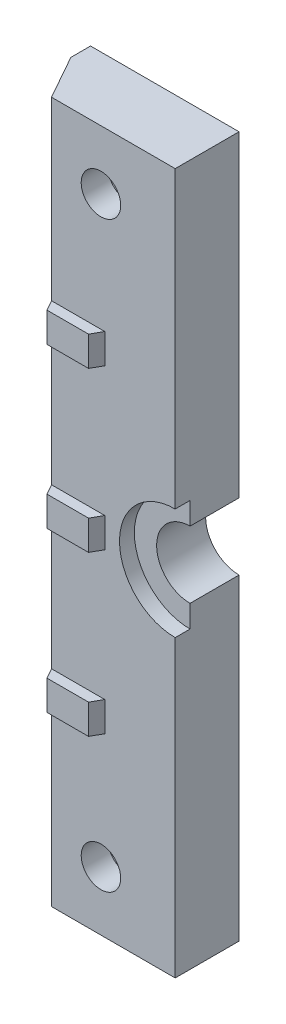
SolidWorks part; units mm, degrees
material "6061-T6 (SS)"
ref_plane "Front Plane" through (0, 0, 0) normal (0, 0, 1) x (1, 0, 0)
ref_plane "Top Plane" through (0, 0, 0) normal (0, 1, 0) x (1, 0, 0)
ref_plane "Right Plane" through (0, 0, 0) normal (1, 0, 0) x (0, 0, -1)
sketch "Sketch1" plane through (0, 0, 0) normal (0, 1, 0) x (1, 0, 0)
  line L0 (0, 0) -> (0, 10.922)
  line L1 (0, 10.922) -> (-25.4, 10.922)
  line L2 (-25.4, 10.922) -> (-25.4, 7.5565)
  line L3 (-25.4, 7.5565) -> (-21.1557, 0)
  line L4 (-21.1557, 0) -> (0, 0)
  dimension "D1" = 25.4
  dimension "D2" = 10.922
  dimension "D3" = 150.678
  dimension "D4" = 3.3655
extrude "Boss-Extrude1" add sketch "Sketch1" along normal blind 119.888
sketch "Sketch2" plane through (0, 0, -10.922) normal (0, 0, -1) x (-1, 0, 0)
  line L0 (12.7, 119.888) -> (12.7, 0) construction
  line L1 (0, 119.888) -> (25.4, 119.888) construction
  line L2 (0, 0) -> (25.4, 0) construction
  line L4 (0, 119.888) -> (0, 0) construction
  line L5 (0, 59.944) -> (25.4, 59.944) construction
  line L6 (25.4, 119.888) -> (25.4, 0) construction
  point P12 (12.7, 10.1155)
  point P14 (12.7, 109.7724)
  dimension "D1" = 49.8285
hole_wizard "CBORE for 1/4 Socket Head Cap Screw1" positions "Sketch2" profile "Sketch3" counterbore size "1/4" standard "ANSI Inch" end condition through all
sketch "Sketch3" plane through (-12.7, 109.7724, -10.922) normal (1, 0, 0) x (0, 1, 0)
  line L0 (0, 0) -> (0, 10.922)
  line L1 (0, 10.922) -> (3.3782, 10.922)
  line L3 (3.3782, 10.922) -> (3.3782, 6.35)
  line L4 (3.3782, 6.35) -> (5.5562, 6.35)
  line L5 (5.5562, 6.35) -> (5.5563, 0)
  line L7 (5.5563, 0) -> (0, 0)
  line L11 (0, -6.35) -> (0, 107.95) construction
  dimension "Thru Hole Dia." = 6.7564
  dimension "Thru Hole Depth" = 10.922
  dimension "C'Bore Dia." = 11.1125
  dimension "C'Bore Depth" = 6.35
sketch "Sketch4" plane through (0, 0, -10.922) normal (0, 0, -1) x (-1, 0, 0)
  line L0 (25.4, 59.944) -> (0, 59.944) construction
  line L1 (25.4, 119.888) -> (25.4, 0) construction
  circle A0 centre (0, 59.944) radius 5.715
  dimension "D2" = 11.43
  dimension "D1" = 25.4
extrude "Cut-Extrude1" cut sketch "Sketch4" against normal through all
ref_plane "Plane1" through (0, 59.944, 0) normal (0, 1, 0) x (1, 0, 0)
sketch "Sketch5" plane through (0, 59.944, 0) normal (0, 1, 0) x (1, 0, 0)
  line L0 (-21.1557, 0) -> (-20.157, -1.778)
  line L1 (-20.157, -1.778) -> (-13.045, -1.778)
  line L2 (-25.4, 7.5565) -> (-21.1557, 0) construction
  line L3 (-21.1557, 0) -> (0, 0) construction
  line L4 (-16.601, -1.778) -> (-16.601, 0) construction
  line L5 (-12.0463, 0) -> (-13.045, -1.778)
  line L6 (-21.1557, 0) -> (-12.0463, 0)
  dimension "D1" = 7.112
  dimension "D2" = 180
  dimension "D3" = 1.778
extrude "Boss-Extrude2" add sketch "Sketch5" along normal blind 2.54 and the other way blind 2.54
pattern_linear "LPattern1" count 2 spacing 27.2542 along (0, -1, 0) count 2 spacing 27.2542 along (0, 1, 0) of "Boss-Extrude2"
sketch "Sketch6" plane through (0, 0, 0) normal (0, 0, 1) x (1, 0, 0)
  circle A0 centre (0, 59.944) radius 9.525
  dimension "D1" = 19.05
extrude "Cut-Extrude2" cut sketch "Sketch6" against normal blind 2.54
